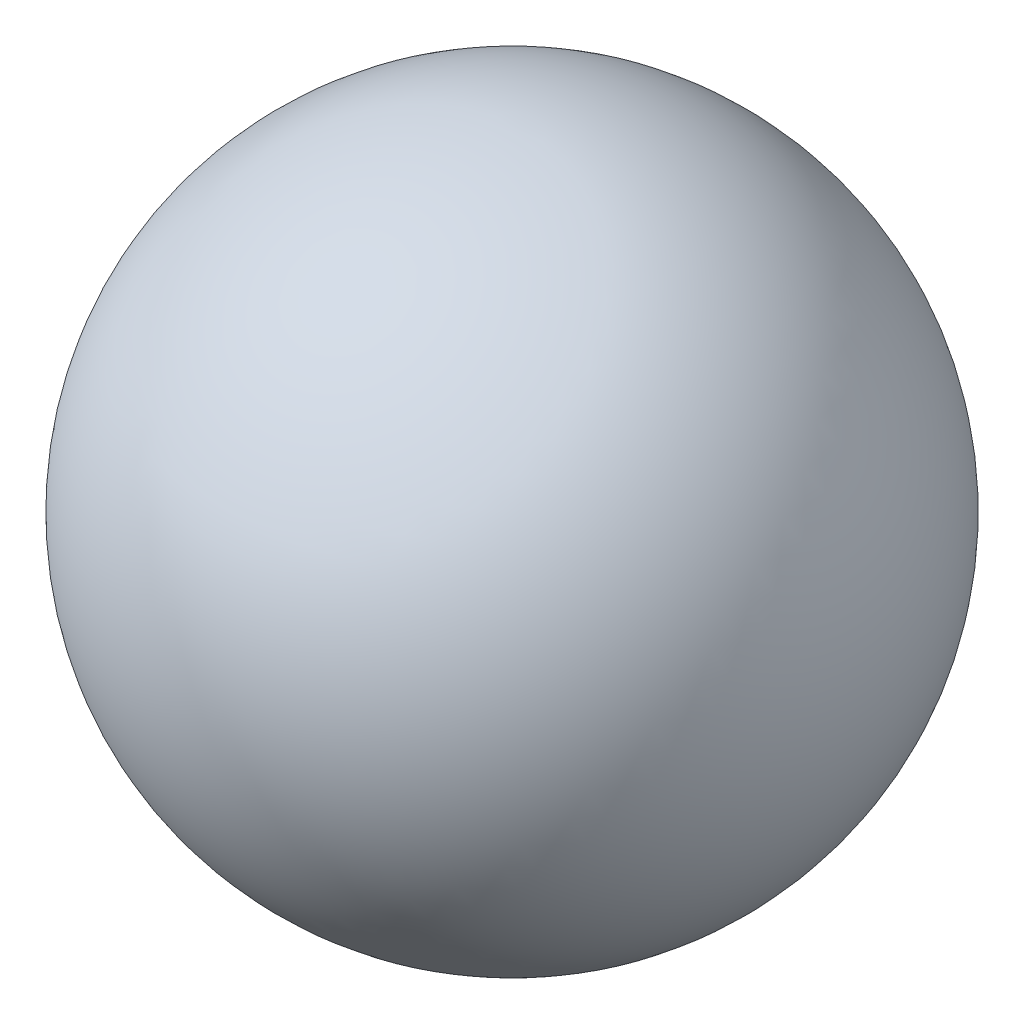
SolidWorks part; units mm, degrees
ref_plane "Спереди" through (0, 0, 0) normal (0, 0, 1) x (1, 0, 0)
ref_plane "Сверху" through (0, 0, 0) normal (0, 1, 0) x (1, 0, 0)
ref_plane "Справа" through (0, 0, 0) normal (1, 0, 0) x (0, 0, -1)
sketch "Эскиз3" [suppressed] plane through (0, 0, 0) normal (0, 0, 1) x (1, 0, 0)
  line L0 (0, 4.75) -> (0, -4.75)
  arc A0 (0, -4.75) -> (0, 4.75) centre (0, 0) ccw
  dimension "D1" = 4.75
revolve "Шарик 9мм" [suppressed] add sketch "Эскиз3" angle 360 about L0
sketch "Эскиз1" plane through (0, 0, 0) normal (0, 0, 1) x (1, 0, 0)
  line L0 (0, 4.5) -> (0, -4.5)
  arc A0 (0, -4.5) -> (0, 4.5) centre (0, 0) ccw
  dimension "D1" = 4.5
revolve "Шарик 9,5мм" [suppressed] add sketch "Эскиз1" angle 360 about L0
sketch "Эскиз4" [suppressed] plane through (0, 0, 0) normal (0, 0, 1) x (1, 0, 0)
  line L0 (0, 5) -> (0, -5)
  arc A0 (0, -5) -> (0, 5) centre (0, 0) ccw
  dimension "D1" = 5
revolve "шарик 10мм" [suppressed] add sketch "Эскиз4" angle 360 about L0
sketch "Эскиз5" [suppressed] plane through (0, 0, 0) normal (0, 0, 1) x (1, 0, 0)
  line L1 (0, 6) -> (0, -6)
  arc A1 (0, -6) -> (0, 6) centre (0, 0) ccw
  dimension "D1" = 6
revolve "Шарик 12мм" [suppressed] add sketch "Эскиз5" angle 360 about L1
sketch "Эскиз7" plane through (0, 0, 0) normal (0, 0, 1) x (1, 0, 0)
  line L0 (0, 7) -> (0, -7)
  arc A0 (0, 7) -> (0, -7) centre (0, 0) cw
  dimension "D1" = 7
revolve "Шарик 14мм" add sketch "Эскиз7" angle 360 about L0
